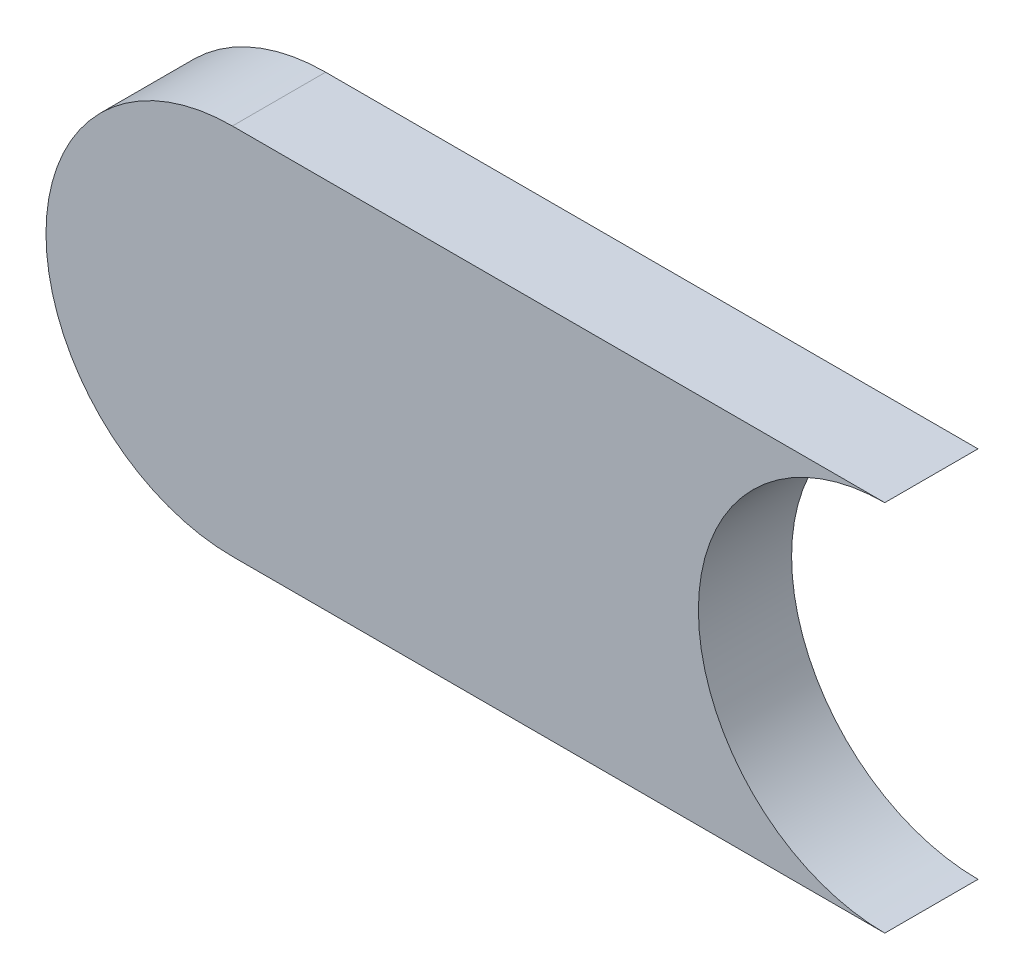
SolidWorks part; units mm, degrees
ref_plane "Front Plane" through (0, 0, 0) normal (0, 0, 1) x (1, 0, 0)
ref_plane "Top Plane" through (0, 0, 0) normal (0, 1, 0) x (1, 0, 0)
ref_plane "Right Plane" through (0, 0, 0) normal (1, 0, 0) x (0, 0, -1)
sketch "Sketch1" plane through (0, 0, 0) normal (0, 0, 1) x (1, 0, 0)
  line L1 (0, 0) -> (88.9, 0)
  line L3 (0, 50.8) -> (88.9, 50.8)
  arc A0 (88.9, 0) -> (88.9, 50.8) centre (88.9, 25.4) cw
  arc A1 (0, 50.8) -> (0, 0) centre (0, 25.4) ccw
  dimension "D1" = 50.8
  dimension "D2" = 88.9
extrude "Boss-Extrude1" add sketch "Sketch1" along normal blind 12.7
